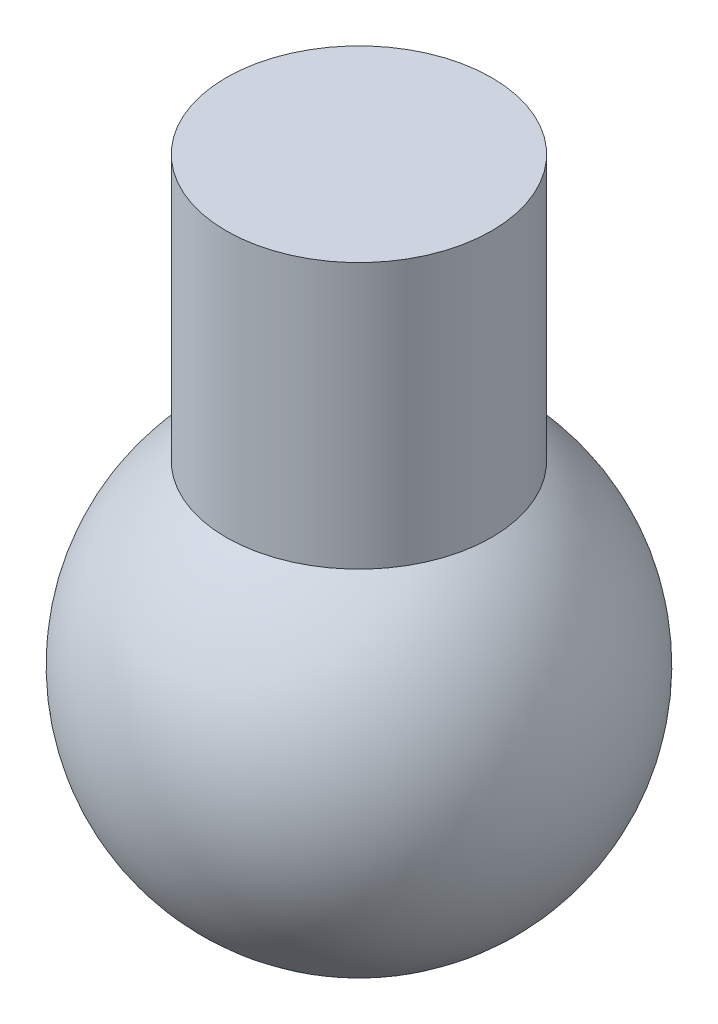
SolidWorks part; units mm, degrees
ref_plane "Front Plane" through (0, 0, 0) normal (0, 0, 1) x (1, 0, 0)
ref_plane "Top Plane" through (0, 0, 0) normal (0, 1, 0) x (1, 0, 0)
ref_plane "Right Plane" through (0, 0, 0) normal (1, 0, 0) x (0, 0, -1)
sketch "Sketch1" plane through (0, 0, 0) normal (0, 0, 1) x (1, 0, 0)
  line L0 (25, 0) -> (-25, 0)
  arc A0 (25, 0) -> (-25, 0) centre (0, 0) ccw
  point P4 (0, 0)
  dimension "D1" = 50
revolve "Revolve1" add sketch "Sketch1" angle 360 about L0
ref_plane "Plane1" through (0, 25, 0) normal (0, 1, 0) x (1, 0, 0)
sketch "Sketch2" plane through (0, 25, 0) normal (0, 1, 0) x (1, 0, 0)
  circle A0 centre (0, 0) radius 15
  dimension "D1" = 30
extrude "Boss-Extrude1" add sketch "Sketch2" along normal blind 25 and the other way up to next
sketch "Sketch3" plane through (0, 0, 0) normal (0, 1, 0) x (1, 0, 0)
  point P0 (0, 0)
sketch "Sketch4" plane through (0, 25, 0) normal (0, 1, 0) x (1, 0, 0)
  point P0 (0, 0)
